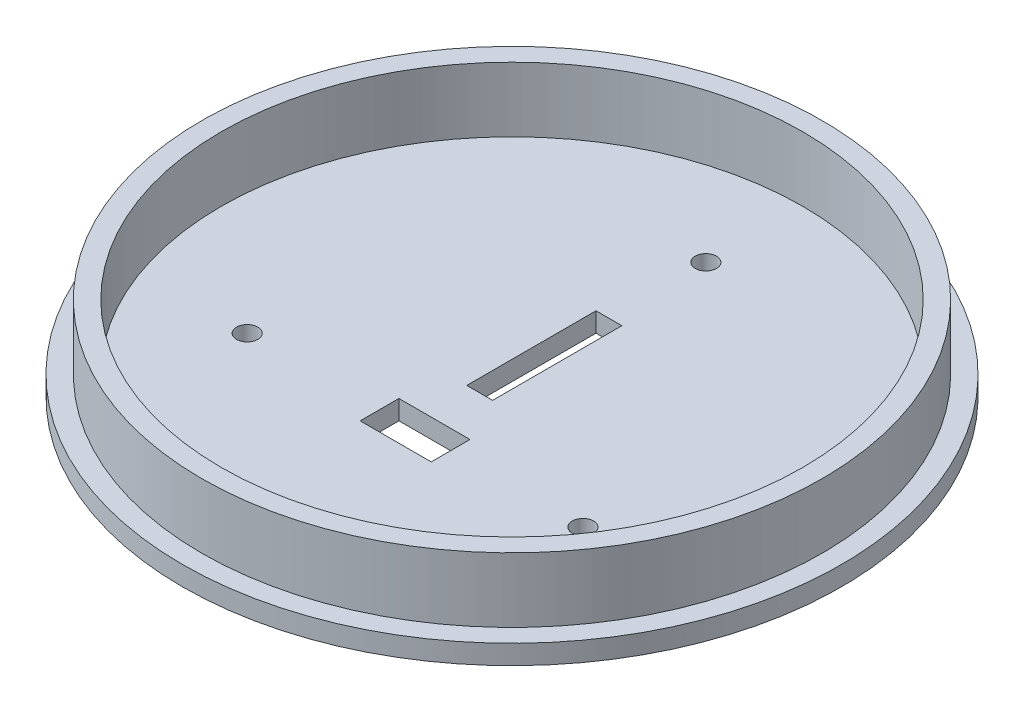
SolidWorks part; units mm, degrees
material "3.0205 (EN-AW 1200)"
ref_plane "Спереди" through (0, 0, 0) normal (0, 0, 1) x (1, 0, 0)
ref_plane "Сверху" through (0, 0, 0) normal (0, 1, 0) x (1, 0, 0)
ref_plane "Справа" through (0, 0, 0) normal (1, 0, 0) x (0, 0, -1)
other "Configuration Table"
sketch "Эскиз1" plane through (0, 0, 0) normal (0, 1, 0) x (1, 0, 0)
  circle A0 centre (0, 0) radius 51
  dimension "D1" = 102
extrude "Бобышка-Вытянуть1" add sketch "Эскиз1" along normal blind 3
sketch "Эскиз2" plane through (0, 3, 0) normal (0, 1, 0) x (1, 0, 0)
  circle A0 centre (0, 0) radius 48
  circle A1 centre (0, 0) radius 45
  circle A2 centre (0, 0) radius 51
  circle A3 centre (0, 0) radius 51
  dimension "D2" = 3
  dimension "D3" = 3
  dimension "D1" = 0
extrude "Бобышка-Вытянуть2" add sketch "Эскиз2" along normal blind 10 contours A0 A1
sketch "Эскиз5" plane through (0, 3, 0) normal (0, 1, 0) x (1, 0, 0)
  line L0 (0, 0) -> (50000, 0) construction
  line L1 (0, 0) -> (0, 50000) construction
  circle A0 centre (0, 0) radius 30 construction
  circle A1 centre (0, 30) radius 1.65
  dimension "D1" = 60
  dimension "D2" = 3.3
extrude "Вырез-Вытянуть1" cut sketch "Эскиз5" against normal blind 10
pattern_circular "Круговой массив1" count 3 over 360 about axis through (0, 0, 0) along (0, 1, 0) of "Вырез-Вытянуть1"
sketch "Эскиз6" plane through (0, 3, 0) normal (0, 1, 0) x (1, 0, 0)
  line L0 (0, -1000) -> (0, 49000) construction
  line L1 (-1025.9808, -15) -> (48974.0192, -15) construction
  line L2 (-2, -5) -> (2, -5)
  line L3 (-2, -5) -> (-2, 15)
  line L4 (-2, 15) -> (2, 15)
  line L5 (2, -5) -> (2, 15)
  line L6 (-2, -5) -> (2, 15) construction
  line L7 (-2, 15) -> (2, -5) construction
  line L8 (-5.5, -12) -> (5.5, -12)
  line L9 (-5.5, -12) -> (-5.5, -18)
  line L10 (-5.5, -18) -> (5.5, -18)
  line L11 (5.5, -12) -> (5.5, -18)
  line L12 (-5.5, -12) -> (5.5, -18) construction
  line L13 (-5.5, -18) -> (5.5, -12) construction
  circle A1 centre (0, 30) radius 1.65 construction
  point P1 (0, 5)
  point P10 (0, -15)
  dimension "D3" = 15
  dimension "D1" = 4
  dimension "D2" = 20
  dimension "D4" = 6
  dimension "D5" = 11
extrude "Вырез-Вытянуть2" cut sketch "Эскиз6" against normal blind 10
